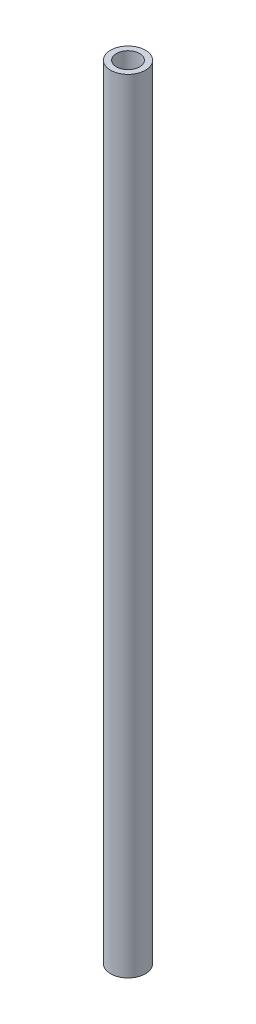
SolidWorks part; units mm, degrees
ref_plane "Front Plane" through (0, 0, 0) normal (0, 0, 1) x (1, 0, 0)
ref_plane "Top Plane" through (0, 0, 0) normal (0, 1, 0) x (1, 0, 0)
ref_plane "Right Plane" through (0, 0, 0) normal (1, 0, 0) x (0, 0, -1)
sketch "Sketch1" plane through (0, 0, 0) normal (0, 0, 1) x (1, 0, 0)
  line L0 (0, -200) -> (0, 100) construction
  line L1 (2, -100) -> (2, 35)
  line L2 (2, 35) -> (3, 35)
  line L3 (3, 35) -> (3, -100)
  line L4 (3, -100) -> (2, -100)
revolve "Revolve1" add sketch "Sketch1" angle 360 about L0
